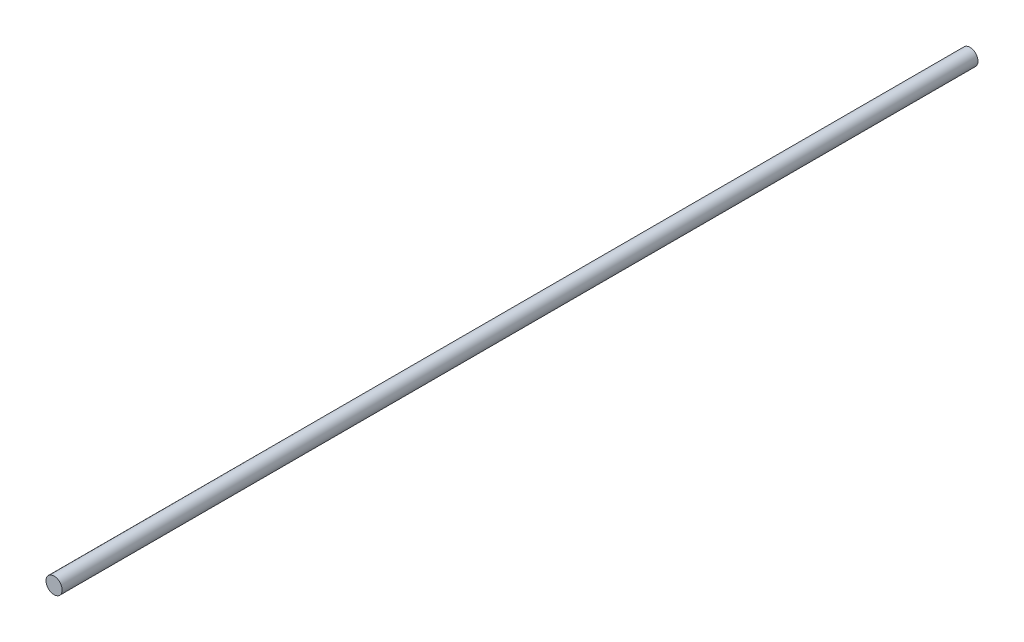
SolidWorks part; units mm, degrees
ref_plane "Plan de face" through (0, 0, 0) normal (0, 0, 1) x (1, 0, 0)
ref_plane "Plan de dessus" through (0, 0, 0) normal (0, 1, 0) x (1, 0, 0)
ref_plane "Plan de droite" through (0, 0, 0) normal (1, 0, 0) x (0, 0, -1)
sketch "Esquisse1" plane through (0, 0, 0) normal (0, 0, 1) x (1, 0, 0)
  circle A0 centre (0, 0) radius 1.5
  dimension "D1" = 3
extrude "Boss.-Extru.1" add sketch "Esquisse1" along normal blind 170
